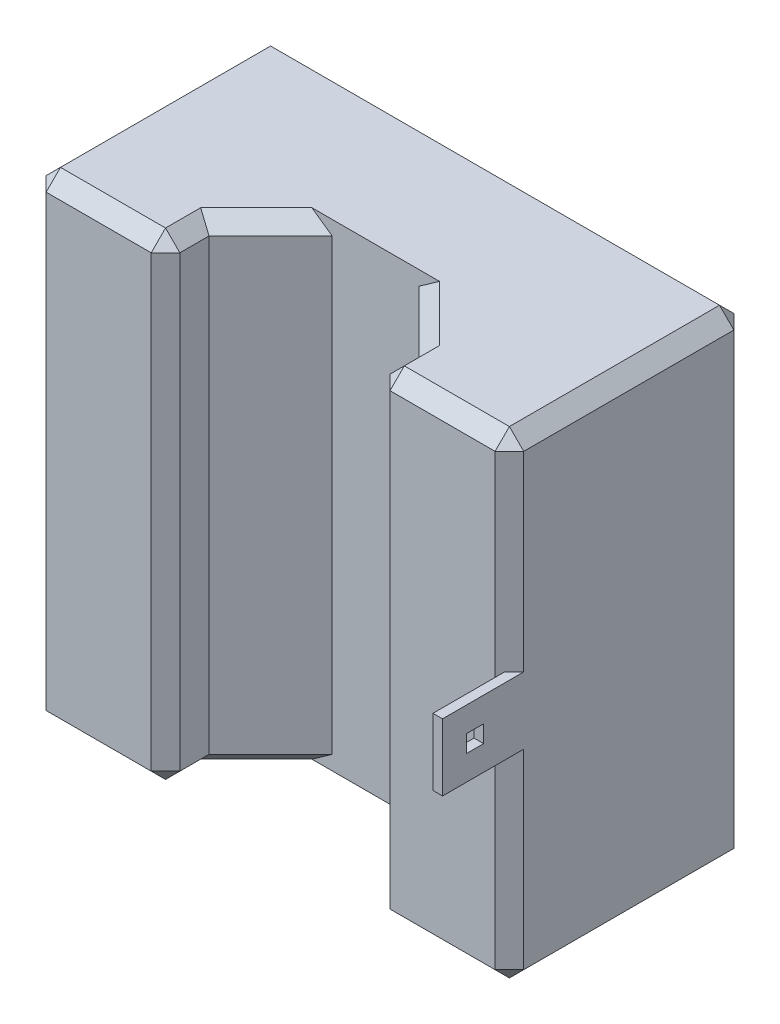
SolidWorks part; units mm, degrees
ref_plane "Front" through (0, 0, 0) normal (0, 0, 1) x (1, 0, 0)
ref_plane "Top" through (0, 0, 0) normal (0, 1, 0) x (1, 0, 0)
ref_plane "Right" through (0, 0, 0) normal (1, 0, 0) x (0, 0, -1)
sketch "Sketch1" plane through (0, 0, 0) normal (0, 0, 1) x (1, 0, 0)
  line L1 (0, 0) -> (50, 0)
  line L2 (0, 0) -> (0, 50)
  line L3 (0, 50) -> (50, 50)
  line L4 (50, 0) -> (50, 50)
  dimension "D1" = 50
extrude "Boss-Extrude1" add sketch "Sketch1" along normal blind 25
sketch "Sketch2" plane through (0, 0, 0) normal (0, -1, 0) x (1, 0, 0)
  line L0 (0, 25) -> (50, 25) construction
  line L1 (29.5563, 36) -> (20.4437, 36)
  line L2 (20.4437, 36) -> (14, 29.5563)
  line L3 (14, 29.5563) -> (14, 20.4437)
  line L4 (14, 20.4437) -> (20.4437, 14)
  line L5 (20.4437, 14) -> (29.5563, 14)
  line L6 (29.5563, 14) -> (36, 20.4437)
  line L7 (36, 20.4437) -> (36, 29.5563)
  line L8 (36, 29.5563) -> (29.5563, 36)
  circle A0 centre (25, 25) radius 11 construction
  dimension "D1" = 22
extrude "Cut-Extrude1" cut sketch "Sketch2" against normal through all
chamfer "Chamfer1" distance 1.5 angle 45 24 edges at (25, 50, 0) (0, 25, 0) (0, 50, 12.5) (32.7782, 50, 17.2218) (36, 50, 22.7218) (7, 50, 25) (17.2218, 50, 17.2218) (14, 50, 22.7218) (36, 25, 25) (43, 50, 25) (50, 50, 12.5) (50, 25, 0) (0, 25, 25) (14, 25, 25) (17.2218, 0, 17.2218) (14, 0, 22.7218) (7, 0, 25) (0, 0, 12.5) (25, 0, 0) (32.7782, 0, 17.2218) (36, 0, 22.7218) (50, 0, 12.5) (50, 25, 25) (43, 0, 25)
sketch "Sketch3" plane through (0, 0, 25) normal (0, 0, 1) x (1, 0, 0)
  line L0 (50, 48.5) -> (50, 1.5) construction
  line L1 (50, 28.5) -> (49, 28.5)
  line L2 (50, 28.5) -> (50, 21.5)
  line L3 (50, 21.5) -> (49, 21.5)
  line L4 (49, 28.5) -> (49, 21.5)
  point P6 (50, 25)
  dimension "D1" = 7
  dimension "D2" = 1
extrude "Boss-Extrude2" add sketch "Sketch3" along normal blind 7 and the other way blind 10
sketch "Sketch4" plane through (50, 0, 0) normal (1, 0, 0) x (0, 0, -1)
  line L0 (-29.5, 25) -> (-32, 25) construction
  line L1 (-29.5, 24.1) -> (-27.7, 24.1)
  line L2 (-29.5, 24.1) -> (-29.5, 25.9)
  line L3 (-29.5, 25.9) -> (-27.7, 25.9)
  line L4 (-27.7, 24.1) -> (-27.7, 25.9)
  line L5 (-32, 21.5) -> (-32, 28.5) construction
  dimension "D1" = 2.5
  dimension "D2" = 1.8
extrude "Cut-Extrude2" cut sketch "Sketch4" against normal blind 7
